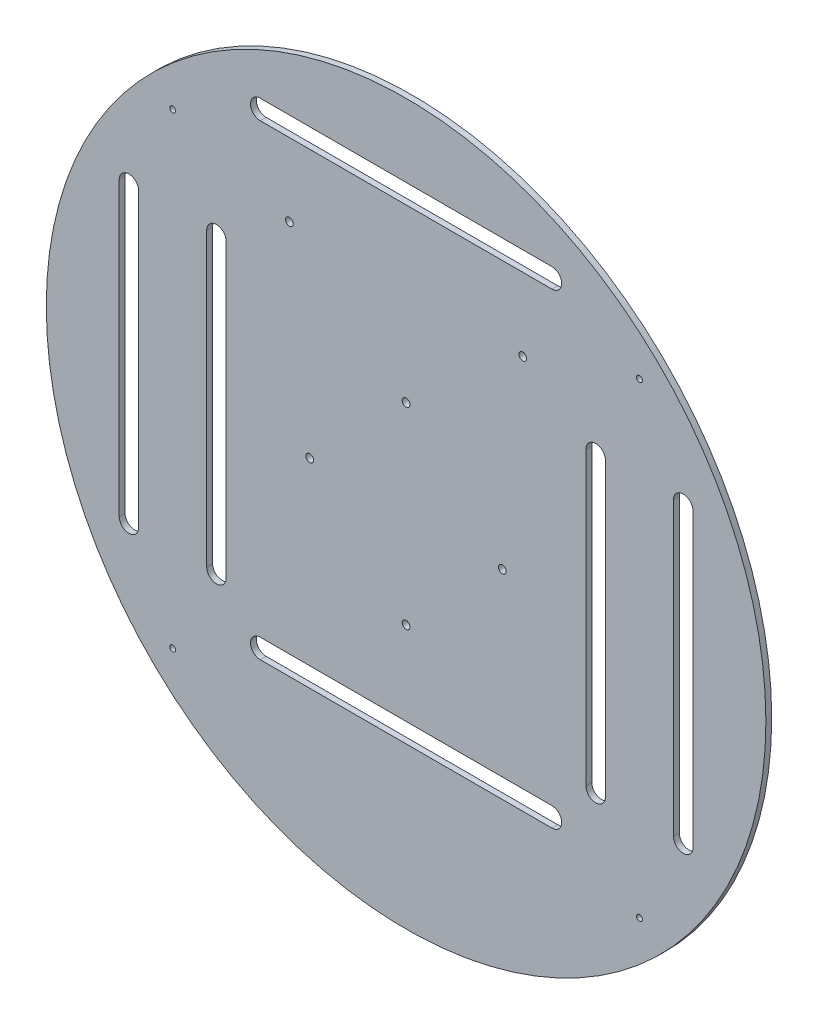
SolidWorks part; units mm, degrees
ref_plane "前视基准面" through (0, 0, 0) normal (0, 0, 1) x (1, 0, 0)
ref_plane "上视基准面" through (0, 0, 0) normal (0, 1, 0) x (1, 0, 0)
ref_plane "右视基准面" through (0, 0, 0) normal (1, 0, 0) x (0, 0, -1)
sketch "草图1" plane through (0, 0, 0) normal (0, 0, 1) x (1, 0, 0)
  line L0 (-294.8988, 0) -> (294.8988, 0) construction
  line L1 (0, -165.4037) -> (0, 165.4037) construction
  line L2 (-97.5, -75) -> (-97.5, 75) construction
  line L3 (-102.5, -75) -> (-102.5, 75)
  line L4 (-92.5, -75) -> (-92.5, 75)
  line L5 (142.5, -75) -> (142.5, 75) construction
  line L6 (147.5, -75) -> (147.5, 75)
  line L7 (137.5, -75) -> (137.5, 75)
  line L8 (-142.5, -75) -> (-142.5, 75) construction
  line L9 (-147.5, -75) -> (-147.5, 75)
  line L10 (-137.5, -75) -> (-137.5, 75)
  line L11 (-75, -97.5) -> (75, -97.5) construction
  line L12 (-75, -102.5) -> (75, -102.5)
  line L13 (-75, -92.5) -> (75, -92.5)
  line L14 (-75, 142.5) -> (75, 142.5) construction
  line L15 (-75, 147.5) -> (75, 147.5)
  line L16 (-75, 137.5) -> (75, 137.5)
  line L17 (97.5, -75) -> (97.5, 75) construction
  line L18 (102.5, -75) -> (102.5, 75)
  line L19 (92.5, -75) -> (92.5, 75)
  circle A0 centre (0, 0) radius 185
  circle A1 centre (-120, 120) radius 1.5
  circle A2 centre (120, 120) radius 1.5
  circle A3 centre (120, -120) radius 1.5
  circle A4 centre (-120, -120) radius 1.5
  arc A5 (-102.5, -75) -> (-92.5, -75) centre (-97.5, -75) ccw
  arc A6 (-92.5, 75) -> (-102.5, 75) centre (-97.5, 75) ccw
  arc A7 (147.5, -75) -> (137.5, -75) centre (142.5, -75) cw
  arc A8 (137.5, 75) -> (147.5, 75) centre (142.5, 75) cw
  arc A11 (-75, -102.5) -> (-75, -92.5) centre (-75, -97.5) cw
  arc A12 (75, -92.5) -> (75, -102.5) centre (75, -97.5) cw
  arc A13 (-75, 147.5) -> (-75, 137.5) centre (-75, 142.5) ccw
  arc A14 (75, 137.5) -> (75, 147.5) centre (75, 142.5) ccw
  arc A15 (-147.5, -75) -> (-137.5, -75) centre (-142.5, -75) ccw
  arc A16 (-137.5, 75) -> (-147.5, 75) centre (-142.5, 75) ccw
  arc A17 (102.5, -75) -> (92.5, -75) centre (97.5, -75) cw
  arc A18 (92.5, 75) -> (102.5, 75) centre (97.5, 75) cw
  point P6 (0, 0)
  point P7 (-120, 120)
  point P9 (0, 0)
  point P12 (0, 0)
  point P13 (-97.5, 0)
  point P15 (0, 0)
  point P16 (-120, -120)
  point P17 (120, -120)
  point P18 (120, 120)
  point P34 (0, 0)
  point P35 (142.5, 0)
  point P37 (0, 142.5)
  point P43 (-142.5, 0)
  point P49 (0, -97.5)
  point P63 (97.5, 0)
  point P68 (143.1187, 0)
  point P84 (0, 0)
  point P85 (0, 45)
  point P102 (0, 45)
  point P110 (0, 45)
  dimension "D1" = 75
  dimension "D3" = 120
  dimension "D7" = 3
  dimension "D8" = 370
  dimension "D9" = 5
  dimension "D4" = 142.5
  dimension "D5" = 97.5
extrude "凸台-拉伸1" add sketch "草图1" along normal blind 3
sketch "草图2" plane through (0, 0, 3) normal (0, 0, 1) x (1, 0, 0)
  line L0 (0, -49.5) -> (0, 49.5)
  line L1 (-49.5, 0) -> (49.5, 0)
  circle A0 centre (0, 49.5) radius 2
  circle A1 centre (0, -49.5) radius 2
  circle A5 centre (49.5, 0) radius 2
  circle A6 centre (-49.5, 0) radius 2
  circle A7 centre (60, 100) radius 2
  circle A8 centre (-60, 100) radius 2
  point P3 (0, 0)
  point P4 (0, 0)
  point P7 (0, 0)
  point P15 (0, 0)
  point P17 (0, 100)
  dimension "D1" = 99
extrude "切除-拉伸1" cut sketch "草图2" against normal blind 10 contours A8 | A7 | A0 | A6 | A1 | A5
